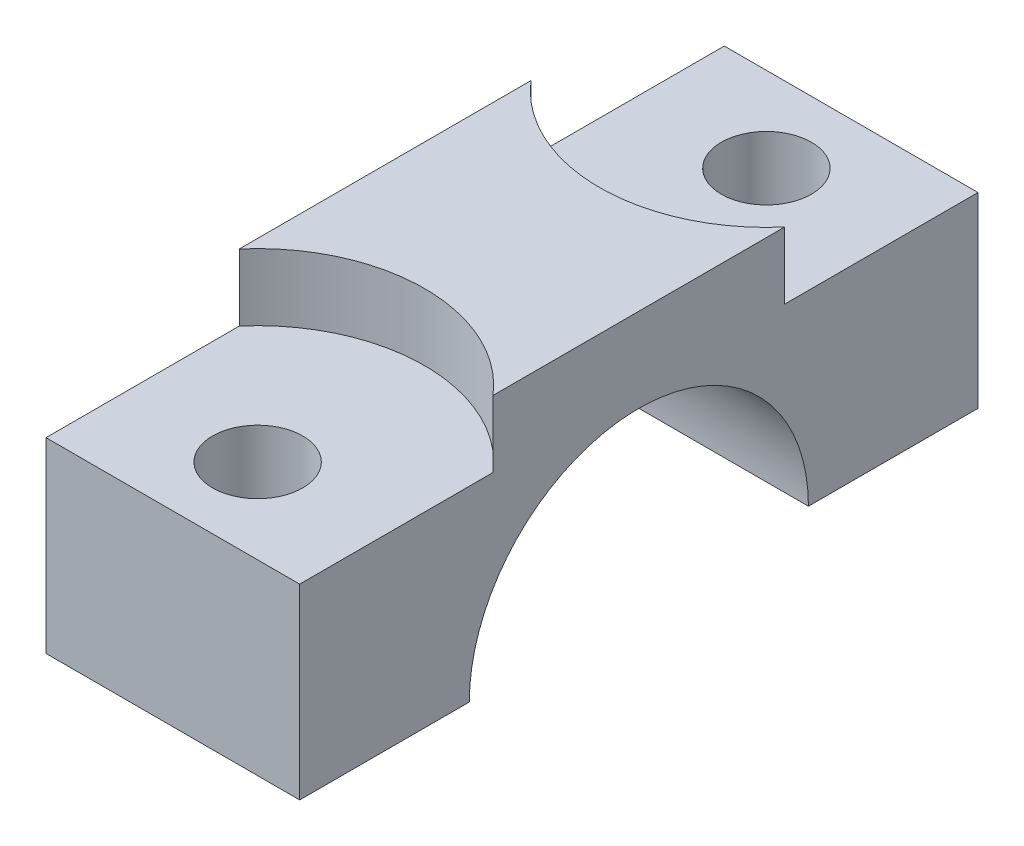
SolidWorks part; units mm, degrees
ref_plane "Front Plane" through (0, 0, 0) normal (0, 0, 1) x (1, 0, 0)
ref_plane "Top Plane" through (0, 0, 0) normal (0, 1, 0) x (1, 0, 0)
ref_plane "Right Plane" through (0, 0, 0) normal (1, 0, 0) x (0, 0, -1)
sketch "Sketch1" plane through (0, 0, 0) normal (1, 0, 0) x (0, 0, -1)
  line L1 (-25.4, 0) -> (25.4, 0)
  line L2 (-25.4, 0) -> (-25.4, 19)
  line L3 (-25.4, 19) -> (25.4, 19)
  line L4 (25.4, 0) -> (25.4, 19)
  circle A0 centre (0, 0) radius 12.7
  dimension "D3" = 25.4
  dimension "D1" = 50.8
  dimension "D2" = 19
extrude "Boss-Extrude1" add sketch "Sketch1" along normal mid plane 19 contours A0 L1 L4 L3 L2
sketch "Sketch4" plane through (0, 0, 0) normal (0, -1, 0) x (1, 0, 0)
  line L0 (0, 25.4) -> (0, 12.7) construction
  line L1 (9.5, 25.4) -> (-9.5, 25.4) construction
  line L2 (9.5, 12.7) -> (-9.5, 12.7) construction
  line L3 (0, -12.7) -> (0, -25.4) construction
  line L4 (9.5, -12.7) -> (-9.5, -12.7) construction
  line L5 (9.5, -25.4) -> (-9.5, -25.4) construction
  point P12 (0, 19.05)
  point P13 (0, -19.05)
hole_wizard "CBORE for M12 Hex Head Cap Screw2" positions "Sketch5" profile "Sketch6" counterbore size "M12" standard "ISO" end condition through all
sketch "Sketch5" plane through (0, 19, 0) normal (0, 1, 0) x (1, 0, 0)
  line L0 (0, 12.7) -> (0, 25.4) construction
  point P0 (0, 19.05)
  point P4 (0, -19.05)
sketch "Sketch6" plane through (0, 19, -19.05) normal (1, 0, 0) x (0, 0, 1)
  line L0 (0, 0) -> (0, 19)
  line L1 (0, 19) -> (3.375, 19)
  line L3 (3.375, 19) -> (3.375, 5)
  line L4 (3.375, 5) -> (12.5, 5)
  line L5 (12.5, 5) -> (12.5, 0)
  line L7 (12.5, 0) -> (0, 0)
  line L11 (0, -6.35) -> (0, 107.95) construction
  dimension "Thru Hole Dia." = 6.75
  dimension "Thru Hole Depth" = 19
  dimension "C'Bore Dia." = 25
  dimension "C'Bore Depth" = 5
scale "Scale1" scale about centroid uniform scaling yes scale factor 0.51948
